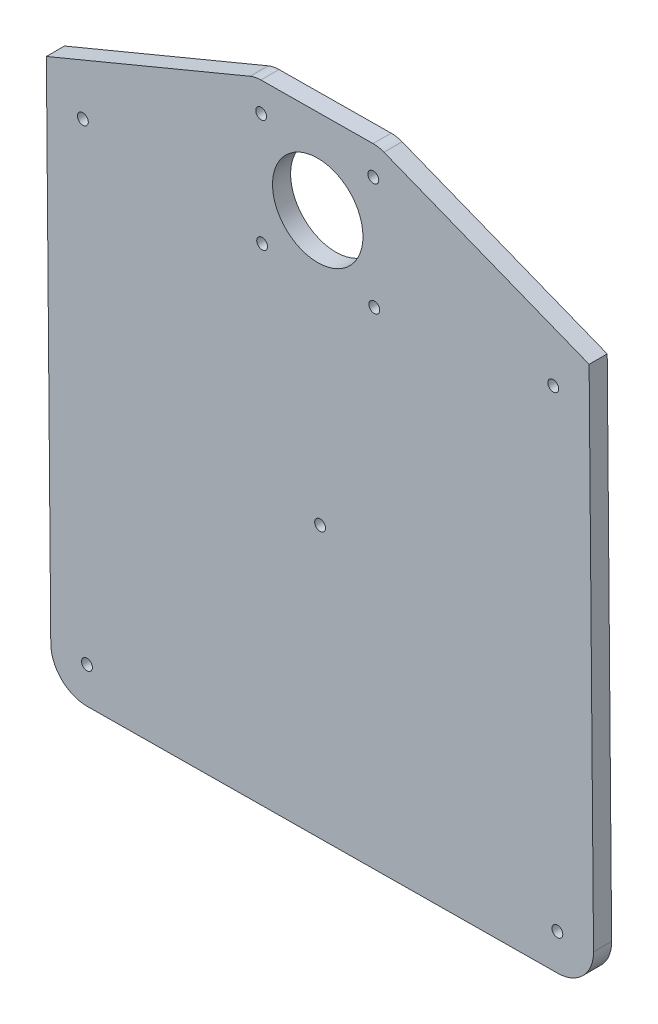
SolidWorks part; units mm, degrees
ref_plane "Front Plane" through (0, 0, 0) normal (0, 0, 1) x (1, 0, 0)
ref_plane "Top Plane" through (0, 0, 0) normal (0, 1, 0) x (1, 0, 0)
ref_plane "Right Plane" through (0, 0, 0) normal (1, 0, 0) x (0, 0, -1)
sketch "Sketch1" plane through (0, 0, 0) normal (0, 1, 0) x (1, 0, 0)
  line L1 (-75, -75) -> (65, -75)
  line L3 (-75, 75) -> (65, 75)
  line L4 (75, -65) -> (75, 65)
  line L5 (-75, -75) -> (75, 75) construction
  line L6 (-75, 75) -> (75, -75) construction
  line L11 (-90.5, -15.5) -> (-59.5, 15.5) construction
  line L12 (-90.5, 15.5) -> (-59.5, -15.5) construction
  line L16 (-97.9134, -18.5069) -> (-75, -75)
  line L17 (-98.5, -15.5) -> (-98.5, 15.5)
  line L18 (-98.5, 0) -> (-75, 0) construction
  line L19 (-97.9134, 18.5069) -> (-75, 75)
  circle A0 centre (-90.5, 15.5) radius 1.5
  circle A1 centre (-90.5, -15.5) radius 1.5
  circle A2 centre (-59.5, -15.5) radius 1.5
  circle A3 centre (-59.5, 15.5) radius 1.5
  circle A4 centre (-75, 0) radius 12.5
  arc A5 (-98.5, -15.5) -> (-97.9134, -18.5069) centre (-90.5, -15.5) ccw
  arc A6 (-98.5, 15.5) -> (-97.9134, 18.5069) centre (-90.5, 15.5) cw
  arc A7 (65, -75) -> (75, -65) centre (65, -65) ccw
  arc A8 (65, 75) -> (75, 65) centre (65, 65) cw
  circle A9 centre (-65, 65) radius 1.5
  circle A10 centre (65, 65) radius 1.5
  circle A11 centre (65, -65) radius 1.5
  circle A12 centre (-65, -65) radius 1.5
  circle A13 centre (0, 0) radius 1.5
  point P0 (0, 0)
  point P6 (-75, 0)
  dimension "D3" = 3
  dimension "D2" = 25
  dimension "D6" = 10
  dimension "D7" = 3
  dimension "D8" = 3
  dimension "D1" = 150
  dimension "D4" = 31
  dimension "D5" = 8
extrude "Boss-Extrude1" add sketch "Sketch1" along normal blind 5
move or copy body "Body-Move/Copy1" bodies to move or copy 101 copy no rotation origin (-6.9519, -2.2564, 4.7564) rotation axis (-0.5807, 0.5757, -0.5757) rotation angle 119.712
move or copy body "Body-Move/Copy2" bodies to move or copy 102 copy no translate (11.6475, 9.2496, 0)
sketch "Sketch2" plane through (0.6545, -74.9971, 0) normal (0.0087, -1, 0) x (1, 0.0087, 0)
  line L0 (0, 2.5) -> (0, -2.5) construction
  line L1 (65, 2.5) -> (-65, 2.5) construction
  line L2 (65, -2.5) -> (-65, -2.5) construction
